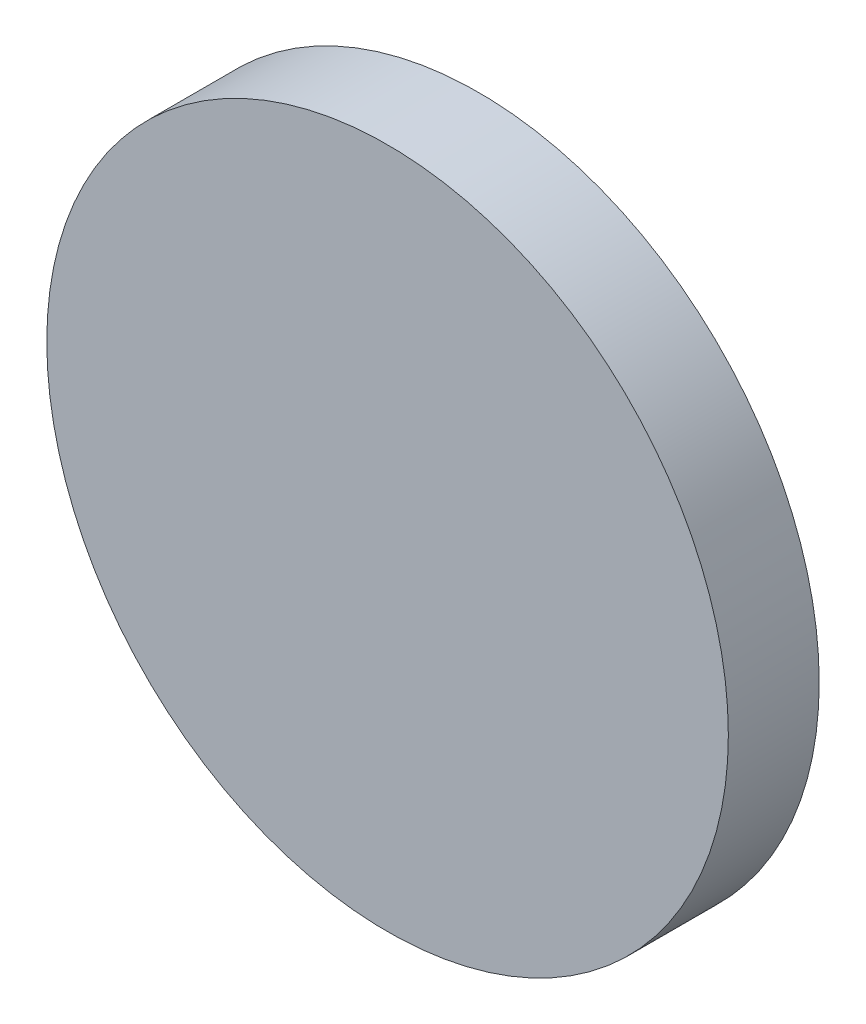
SolidWorks part; units mm, degrees
ref_plane "前视基准面" through (0, 0, 0) normal (0, 0, 1) x (1, 0, 0)
ref_plane "上视基准面" through (0, 0, 0) normal (0, 1, 0) x (1, 0, 0)
ref_plane "右视基准面" through (0, 0, 0) normal (1, 0, 0) x (0, 0, -1)
sketch "草图1" plane through (0, 0, 0) normal (0, 0, 1) x (1, 0, 0)
  circle A0 centre (0, 0) radius 60
extrude "凸台-拉伸1" add sketch "草图1" along normal blind 16
